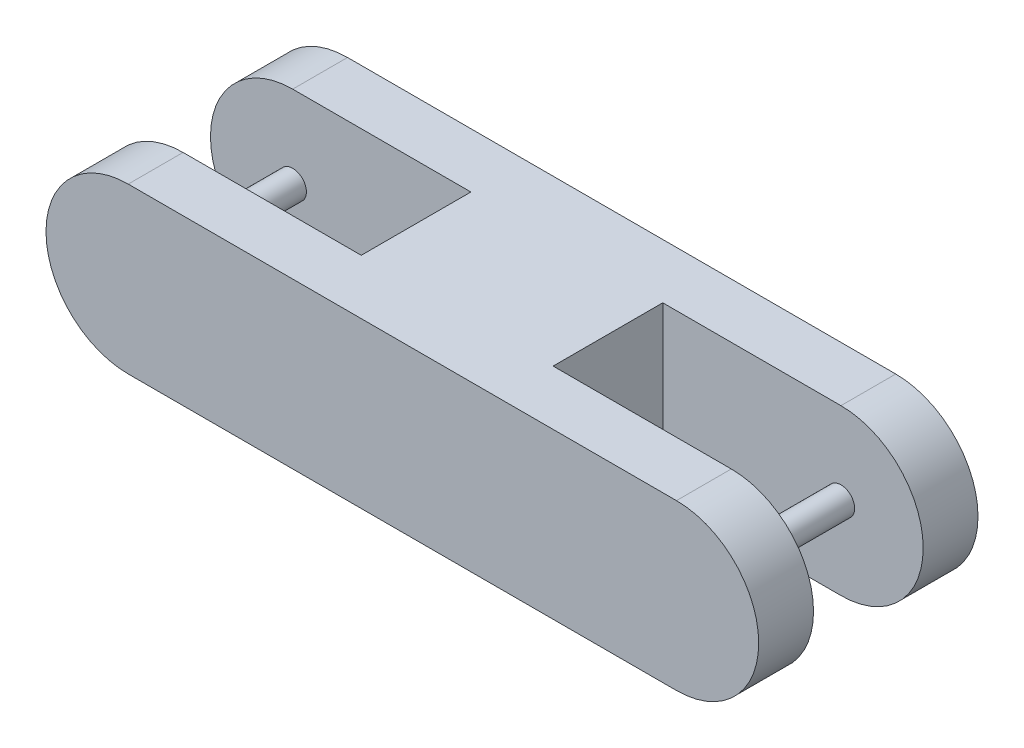
SolidWorks part; units mm, degrees
ref_plane "Front Plane" through (0, 0, 0) normal (0, 0, 1) x (1, 0, 0)
ref_plane "Top Plane" through (0, 0, 0) normal (0, 1, 0) x (1, 0, 0)
ref_plane "Right Plane" through (0, 0, 0) normal (1, 0, 0) x (0, 0, -1)
sketch "Sketch1" plane through (0, 0, 0) normal (0, 0, 1) x (1, 0, 0)
  line L0 (0, 38.1) -> (254, 38.1)
  line L1 (0, 38.1) -> (0, -38.1) construction
  line L2 (0, -38.1) -> (254, -38.1)
  line L3 (254, 38.1) -> (254, -38.1) construction
  arc A0 (0, 38.1) -> (0, -38.1) centre (0, 0) ccw
  arc A1 (254, -38.1) -> (254, 38.1) centre (254, 0) ccw
  point P9 (0, 0)
  point P10 (254, 0)
  point P11 (0, 0)
  point P12 (-90.0062, 90.9041)
  point P13 (0, 0)
  dimension "D1" = 76.2
  dimension "D2" = 76.2
  dimension "D3" = 254
extrude "Boss-Extrude1" add sketch "Sketch1" along normal blind 101.6
sketch "Sketch2" plane through (0, 38.1, 0) normal (0, 1, 0) x (1, 0, 0)
  line L3 (-38.1, -50.8) -> (292.1, -50.8) construction
  line L4 (-38.1, 0) -> (-38.1, -101.6) construction
  line L5 (292.1, -101.6) -> (292.1, 0) construction
sketch "Sketch3" plane through (0, 0, 101.6) normal (0, 0, 1) x (1, 0, 0)
  line L6 (-38.1, 38.1) -> (292.1, 38.1) construction
  line L7 (-82.55, -38.1) -> (82.55, -38.1)
  line L8 (-82.55, -38.1) -> (-82.55, 38.1)
  line L9 (-82.55, 38.1) -> (82.55, 38.1)
  line L10 (82.55, -38.1) -> (82.55, 38.1)
  line L11 (-82.55, -38.1) -> (82.55, 38.1) construction
  line L12 (-82.55, 38.1) -> (82.55, -38.1) construction
  point P0 (0, 0)
  dimension "D1" = 165.1
extrude "Cut-Extrude1" cut sketch "Sketch3" against normal blind 50.8 from offset 25.4 offset against normal yes
sketch "Sketch4" plane through (0, 0, 101.6) normal (0, 0, 1) x (1, 0, 0)
  line L0 (127, 38.1) -> (127, -38.1) construction
  line L1 (-38.1, 38.1) -> (292.1, 38.1) construction
  line L2 (0, -38.1) -> (254, -38.1) construction
ref_plane "Plane1" through (127, 0, 0) normal (1, 0, 0) x (0, 0, -1)
mirror "Mirror1" about plane through (127, 0, 0) normal (1, 0, 0) of "Cut-Extrude1"
sketch "Sketch6" plane through (0, 0, 25.4) normal (0, 0, 1) x (1, 0, 0)
  circle A0 centre (0, 0) radius 6.35
  dimension "D1" = 12.7
extrude "Boss-Extrude2" add sketch "Sketch6" along normal up to next
mirror "Mirror2" about plane through (127, 0, 0) normal (1, 0, 0) of "Boss-Extrude2"
